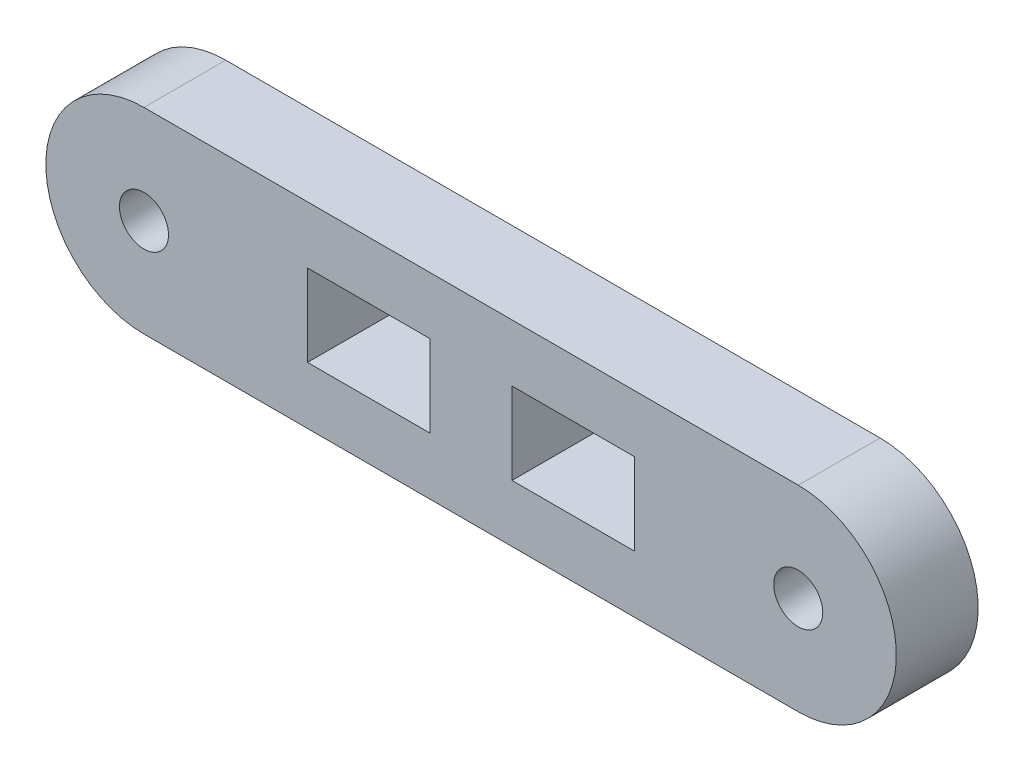
SolidWorks part; units mm, degrees
ref_plane "Plan de face" through (0, 0, 0) normal (0, 0, 1) x (1, 0, 0)
ref_plane "Plan de dessus" through (0, 0, 0) normal (0, 1, 0) x (1, 0, 0)
ref_plane "Plan de droite" through (0, 0, 0) normal (1, 0, 0) x (0, 0, -1)
sketch "Esquisse1" plane through (0, 0, 0) normal (0, 0, 1) x (1, 0, 0)
  line L0 (40, 0) -> (0, 0) construction
  line L1 (40, -6) -> (0, -6)
  line L2 (0, 0) -> (40, 0) construction
  line L3 (40, 6) -> (0, 6)
  line L4 (30, -2.5) -> (22.5, -2.5)
  line L5 (22.5, -2.5) -> (22.5, 2.5)
  line L6 (22.5, 2.5) -> (30, 2.5)
  line L7 (30, 2.5) -> (30, -2.5)
  line L8 (10, 2.5) -> (10, -2.5)
  line L9 (17.5, 2.5) -> (10, 2.5)
  line L10 (17.5, -2.5) -> (17.5, 2.5)
  line L11 (10, -2.5) -> (17.5, -2.5)
  line L12 (20, 6) -> (20, -6) construction
  arc A0 (40, -6) -> (40, 6) centre (40, 0) ccw
  arc A1 (0, 6) -> (0, -6) centre (0, 0) ccw
  circle A5 centre (40, 0) radius 1.5
  circle A6 centre (0, 0) radius 1.5
  point P0 (20, 0)
  dimension "D1" = 40
  dimension "D2" = 3
  dimension "D3" = 6
  dimension "D4" = 2.5
  dimension "D6" = 7.5
  dimension "D7" = 5
extrude "Boss.-Extru.1" add sketch "Esquisse1" along normal blind 5
